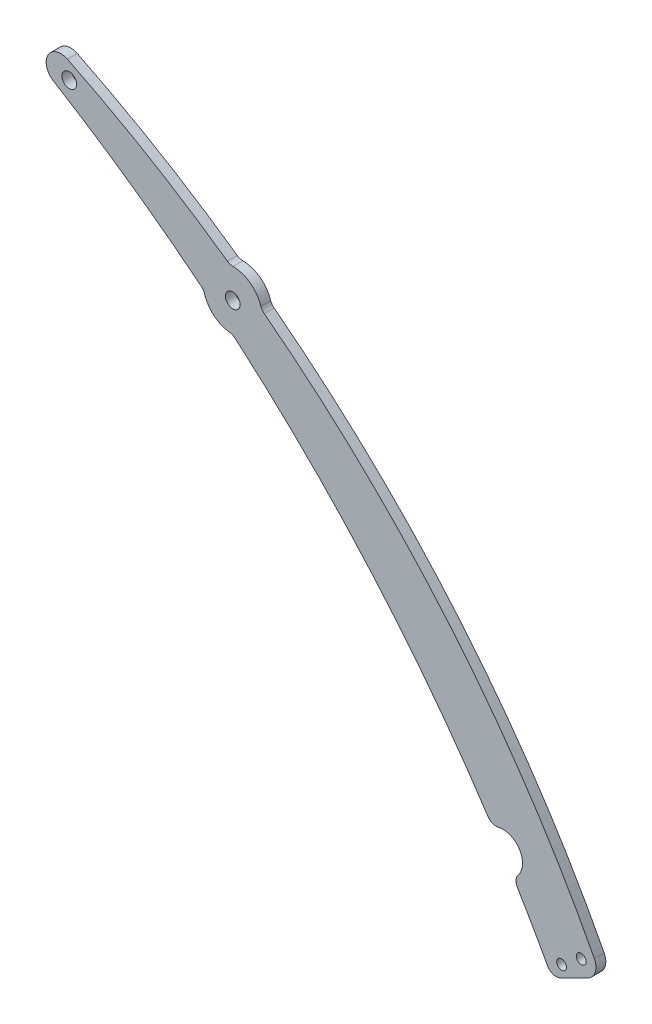
SolidWorks part; units mm, degrees
ref_plane "前视基准面" through (0, 0, 0) normal (0, 0, 1) x (1, 0, 0)
ref_plane "上视基准面" through (0, 0, 0) normal (0, 1, 0) x (1, 0, 0)
ref_plane "右视基准面" through (0, 0, 0) normal (1, 0, 0) x (0, 0, -1)
sketch "草图1" plane through (0, 0, 0) normal (0, 0, 1) x (1, 0, 0)
  line L0 (107.3025, -106.33) -> (101.7379, -109.1266)
  circle A0 centre (0, 0) radius 1.5
  arc A1 (1.322, 2.693) -> (-1.5587, -2.5633) centre (0, 0) ccw
  arc A2 (1.322, 2.693) -> (33.9065, -16.6345) centre (-104.4416, -212.7462) cw
  arc A3 (-1.5587, -2.5633) -> (28.5891, -23.732) centre (-147.0384, -241.8031) cw
  arc A4 (99.0818, -108.2932) -> (101.7379, -109.1266) centre (100.8398, -107.3396) ccw
  arc A5 (108.6186, -102.2685) -> (107.3025, -106.33) centre (105.9554, -103.6495) cw
  circle A7 centre (105.9554, -103.6495) radius 1
  circle A8 centre (101.9554, -106.6495) radius 1
  arc A9 (89.0821, -88.8702) -> (93.1109, -95.2778) centre (90, -92.7634) cw
  arc A10 (92.9522, -97.5653) -> (99.0818, -108.2932) centre (-147.0384, -241.8031) cw
  arc A11 (89.0821, -88.8702) -> (86.9518, -88.022) centre (88.6231, -86.9235) cw
  arc A12 (93.1109, -95.2778) -> (92.9522, -97.5653) centre (94.6664, -96.535) ccw
  circle A13 centre (35, -23) radius 1.5
  arc A14 (29.251, -24.7173) -> (34.3572, -28.9655) centre (35, -23) ccw
  arc A15 (41.4016, -22.1425) -> (108.6186, -102.2685) centre (-104.4416, -212.7462) cw
  arc A16 (40.7127, -21.1656) -> (35.0445, -17.0002) centre (35, -23) ccw
  arc A17 (35.4464, -29.4371) -> (86.9518, -88.022) centre (-147.0384, -241.8031) cw
  arc A18 (29.251, -24.7173) -> (28.5891, -23.732) centre (27.3347, -25.2897) ccw
  arc A19 (34.3572, -28.9655) -> (35.4464, -29.4371) centre (34.1429, -30.954) cw
  arc A20 (41.4016, -22.1425) -> (40.7127, -21.1656) centre (42.617, -20.5542) cw
  arc A21 (33.9065, -16.6345) -> (35.0445, -17.0002) centre (35.0594, -15.0002) ccw
  point P16 (100, -110)
  point P19 (110, -104.9743)
  point P26 (92.1049, -96.1648)
  point P36 (34.9361, -28.9997)
  point P39 (40.8647, -21.7329)
  dimension "D1" = 3
  dimension "D2" = 6
  dimension "D3" = 240
  dimension "D4" = 280
  dimension "D5" = 100
  dimension "D8" = 2
  dimension "D9" = 3
  dimension "D10" = 2
  dimension "D11" = 2
  dimension "D14" = 4
  dimension "D16" = 2
  dimension "D17" = 2
  dimension "D18" = 3
  dimension "D19" = 12
  dimension "D22" = 2
  dimension "D6" = 110
  dimension "D7" = 110
  dimension "D12" = 4
  dimension "D13" = 3
  dimension "D15" = 90
  dimension "D20" = 35
  dimension "D21" = 23
extrude "凸台-拉伸1" add sketch "草图1" along normal blind 2
scale "缩放比例1" scale about centroid uniform scaling yes scale factor 2
sketch "草图2" plane through (0, 0, 3) normal (0, 0, 1) x (1, 0, 0)
  circle A1 centre (8.6255, 5.6344) radius 3
  circle A2 centre (8.6255, 5.6344) radius 80
  circle A4 centre (-57.9676, 49.9667) radius 3
sketch "草图3" plane through (0, 0, -1) normal (0, 0, -1) x (-1, 0, 0)
  circle A0 centre (58.5431, 54.6554) radius 1.6271
  circle A1 centre (61.2094, 50.8664) radius 4.2343
  circle M2 centre (61.3786, 51.6279) radius 3
extrude "凸台-拉伸3" add sketch "草图3" against normal blind 4 contours A0 A1 M2 | A0 M2 | A0 A1 M2 | A0 M2
extrude "切除-拉伸1" cut sketch "草图2" against normal blind 4 contours A4
